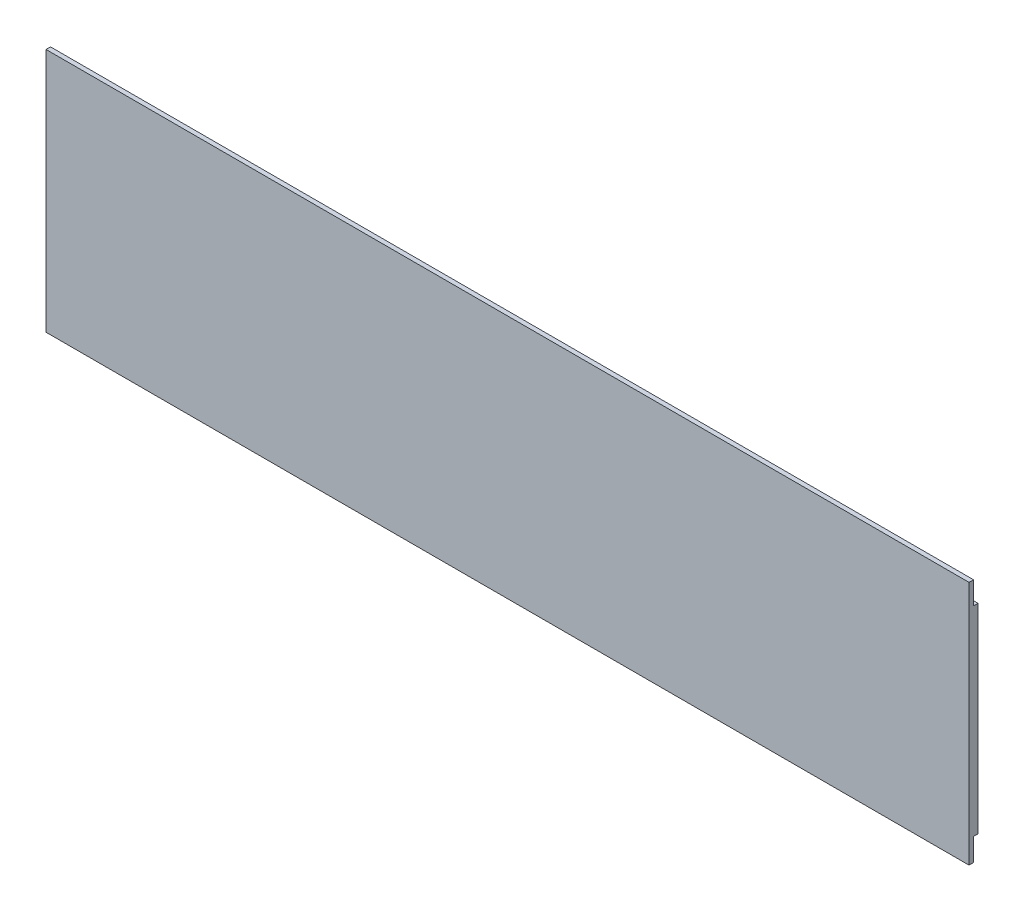
SolidWorks part; units mm, degrees
ref_plane "Front Plane" through (0, 0, 0) normal (0, 0, 1) x (1, 0, 0)
ref_plane "Top Plane" through (0, 0, 0) normal (0, 1, 0) x (1, 0, 0)
ref_plane "Right Plane" through (0, 0, 0) normal (1, 0, 0) x (0, 0, -1)
sketch "Sketch1" plane through (0, 0, 0) normal (0, 0, 1) x (1, 0, 0)
  line L1 (0, 0) -> (326.228, 0)
  line L2 (0, 0) -> (0, 86.5662)
  line L3 (0, 86.5662) -> (326.228, 86.5662)
  line L4 (326.228, 0) -> (326.228, 86.5662)
  line L5 (326.228, -2.2855) -> (326.228, 8) construction
extrude "Boss-Extrude1" add sketch "Sketch1" along normal blind 3.175
sketch "Sketch3" plane through (0, 0, 0) normal (0, 0, -1) x (-1, 0, 0)
  line L0 (0, 86.5662) -> (0, 0) construction
  line L1 (-326.228, 0) -> (0, 0)
  line L2 (-326.228, 0) -> (-326.228, 8)
  line L3 (-326.228, 8) -> (0, 8)
  line L4 (0, 0) -> (0, 8)
  line L6 (-326.228, 86.5662) -> (0, 86.5662)
  line L7 (-326.228, 86.5662) -> (-326.228, 78.5662)
  line L8 (-326.228, 78.5662) -> (0, 78.5662)
  line L9 (0, 86.5662) -> (0, 78.5662)
  dimension "D1" = 8
extrude "Cut-Extrude2" cut sketch "Sketch3" against normal blind 1.5875
